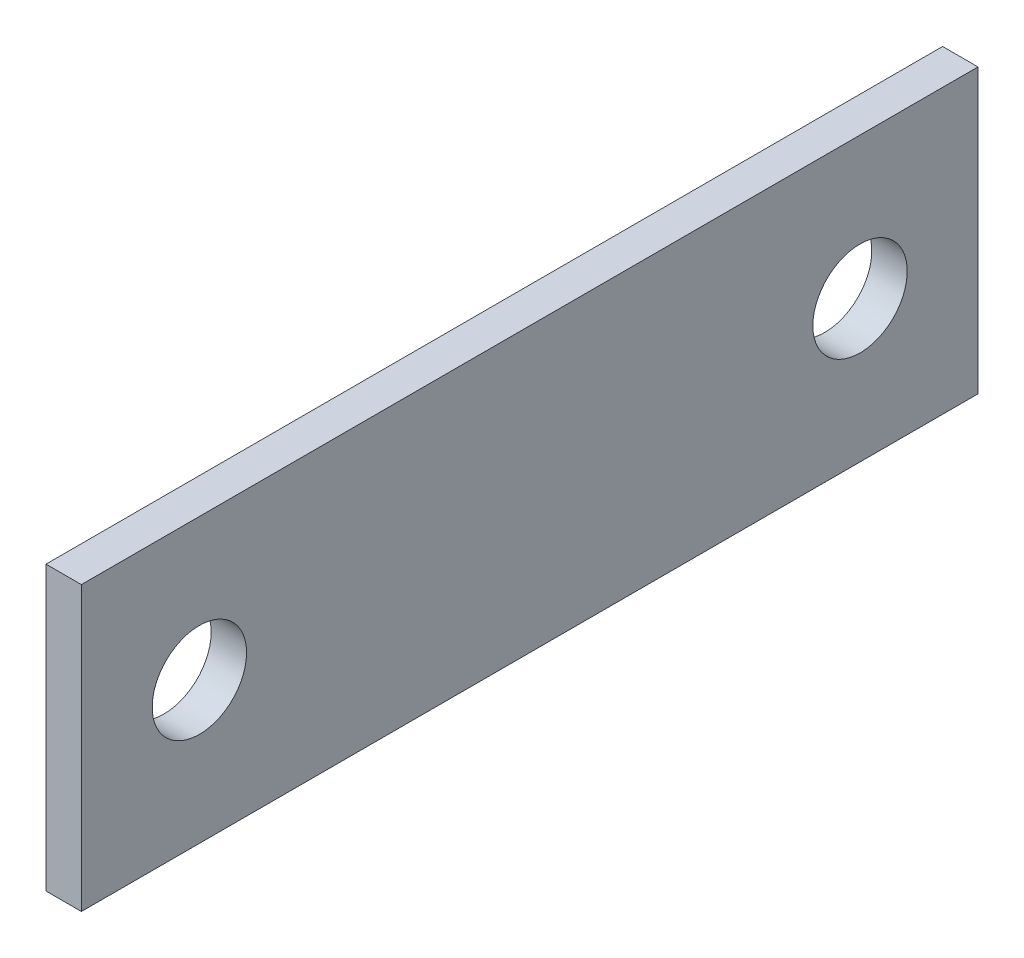
SolidWorks part; units mm, degrees
ref_plane "Plano frontal" through (0, 0, 0) normal (0, 0, 1) x (1, 0, 0)
ref_plane "Plano superior" through (0, 0, 0) normal (0, 1, 0) x (1, 0, 0)
ref_plane "Plano direito" through (0, 0, 0) normal (1, 0, 0) x (0, 0, -1)
sketch "Esboço1" plane through (0, 0, 0) normal (1, 0, 0) x (0, 0, -1)
  line L0 (-19, -6) -> (-19, 6)
  line L1 (-19, -6) -> (19, -6)
  line L2 (-19, 6) -> (19, 6)
  line L3 (19, -6) -> (19, 6)
  line L4 (-19, -6) -> (19, 6) construction
  line L5 (-19, 6) -> (19, -6) construction
  line L6 (0, 0) -> (0, 16.557) construction
  circle A0 centre (-14, 0) radius 2
  circle A1 centre (14, 0) radius 2
  point P1 (0, 0)
  dimension "D3" = 4
  dimension "D1" = 12
  dimension "D2" = 38
  dimension "D4" = 6
  dimension "D5" = 5
extrude "Ressalto-extrusão1" add sketch "Esboço1" along normal blind 1.5
